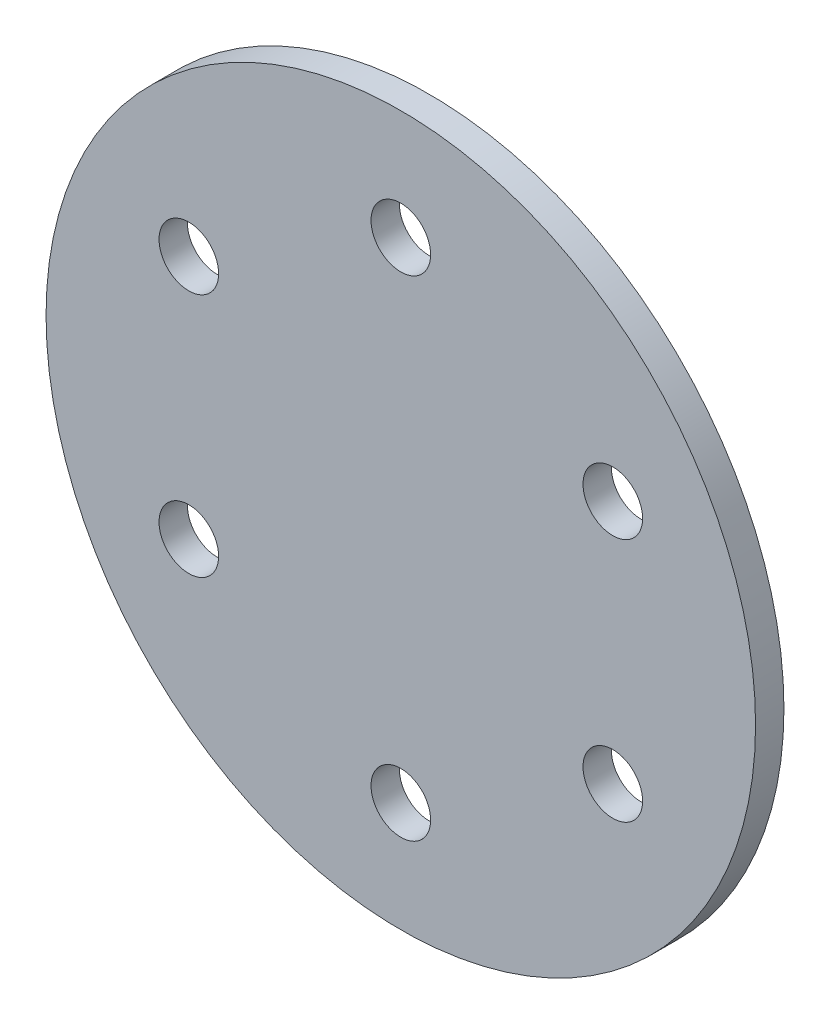
SolidWorks part; units mm, degrees
ref_plane "前视基准面" through (0, 0, 0) normal (0, 0, 1) x (1, 0, 0)
ref_plane "上视基准面" through (0, 0, 0) normal (0, 1, 0) x (1, 0, 0)
ref_plane "右视基准面" through (0, 0, 0) normal (1, 0, 0) x (0, 0, -1)
other "Configuration Table"
sketch "草图1" plane through (0, 0, 0) normal (0, 0, 1) x (1, 0, 0)
  circle A0 centre (0, 0) radius 17.25 construction
  circle A1 centre (0, 17.25) radius 2.1
  circle A2 centre (14.9389, 8.625) radius 2.1
  circle A3 centre (14.9389, -8.625) radius 2.1
  circle A4 centre (0, -17.25) radius 2.1
  circle A5 centre (-14.9389, -8.625) radius 2.1
  circle A6 centre (-14.9389, 8.625) radius 2.1
  circle A7 centre (0, 0) radius 25
  point P17 (0, 0)
  dimension "D1" = 34.5
  dimension "D2" = 4.2
  dimension "D4" = 50
  dimension "D3" = 6
extrude "凸台-拉伸1" add sketch "草图1" along normal blind 2
sketch "草图3" plane through (0, 0, 2) normal (0, 0, 1) x (1, 0, 0)
  circle A0 centre (0, 17.25) radius 3.5
  dimension "D1" = 7
